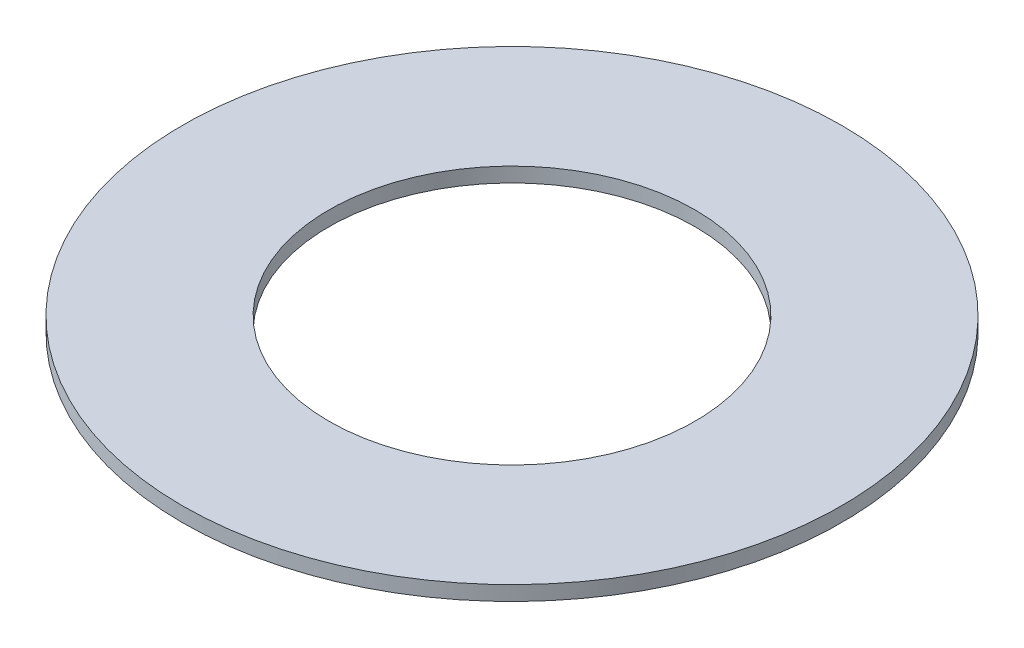
SolidWorks part; units mm, degrees
ref_plane "Ebene vorne" through (0, 0, 0) normal (0, 0, 1) x (1, 0, 0)
ref_plane "Ebene oben" through (0, 0, 0) normal (0, 1, 0) x (1, 0, 0)
ref_plane "Ebene rechts" through (0, 0, 0) normal (1, 0, 0) x (0, 0, -1)
sketch "Skizze1" plane through (0, 0, 0) normal (0, 1, 0) x (1, 0, 0)
  circle A0 centre (0, 0) radius 25
  circle A1 centre (0, 0) radius 45
  dimension "D1" = 50
  dimension "D2" = 90
extrude "Aufsatz-Linear austragen1" add sketch "Skizze1" along normal blind 2
